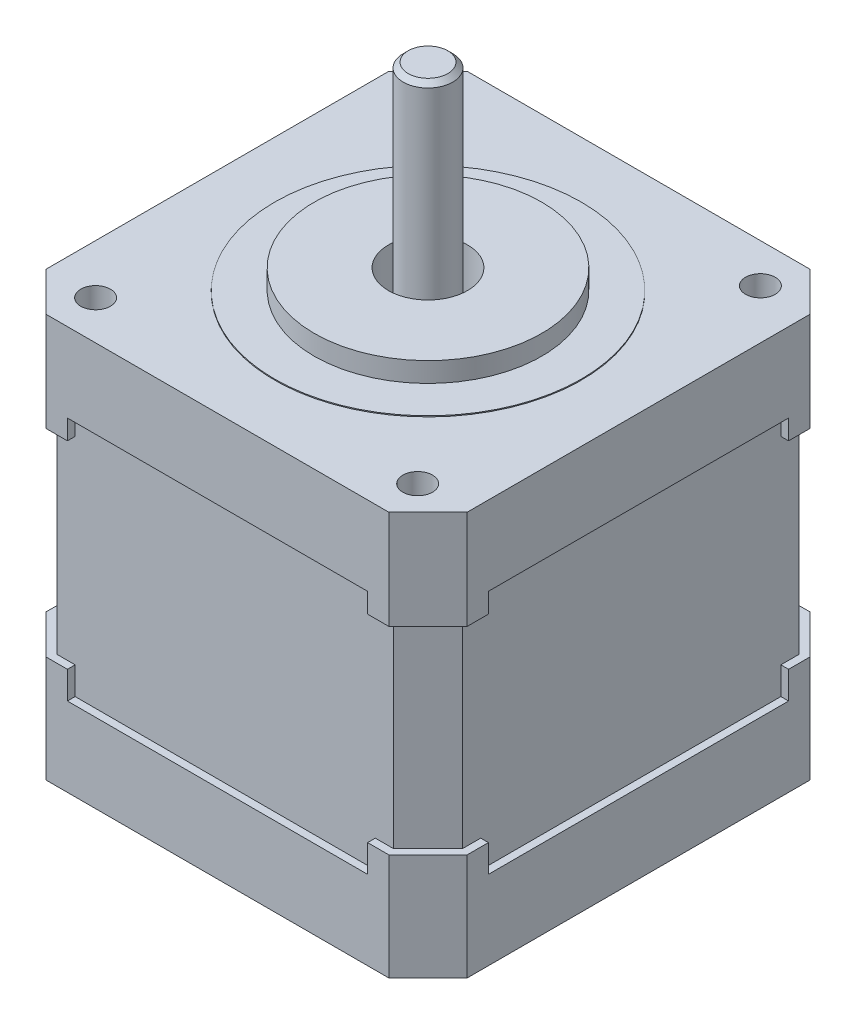
SolidWorks part; units mm, degrees
ref_plane "Alzado" through (0, 0, 0) normal (0, 0, 1) x (1, 0, 0)
ref_plane "Planta" through (0, 0, 0) normal (0, 1, 0) x (1, 0, 0)
ref_plane "Vista lateral" through (0, 0, 0) normal (1, 0, 0) x (0, 0, -1)
sketch "Croquis1" plane through (0, 0, 0) normal (0, 1, 0) x (1, 0, 0)
  line L0 (20.5, 17) -> (17, 20.5)
  line L1 (-17, -20.5) -> (17, -20.5)
  line L2 (-20.5, -17) -> (-20.5, 17)
  line L3 (-17, 20.5) -> (17, 20.5)
  line L4 (20.5, -17) -> (20.5, 17)
  line L5 (-20.5, -20.5) -> (20.5, 20.5) construction
  line L6 (-20.5, 20.5) -> (20.5, -20.5) construction
  line L7 (-20.5, 17) -> (-17, 20.5)
  line L8 (-17, -20.5) -> (-20.5, -17)
  line L9 (17, -20.5) -> (20.5, -17)
  point P0 (0, 0)
  dimension "D1" = 41
  dimension "D2" = 41
extrude "Saliente-Extruir2" add sketch "Croquis1" along normal blind 10
shell "Vaciado6" thickness 0.78
sketch "Croquis2" plane through (21.28, 0, 0) normal (1, 0, 0) x (0, 0, -1)
  line L1 (-17.3231, 10) -> (17.3231, 10) construction
  line L2 (-15.1731, 10) -> (-15.1731, 7.22)
  line L3 (-15.1731, 7.22) -> (15.1731, 7.22)
  line L5 (15.1731, 7.22) -> (15.1731, 10)
  line L6 (-17.3231, 10) -> (-17.3231, -0.78) construction
  line L7 (17.3231, 10) -> (17.3231, -0.78) construction
  line L8 (-17.3231, -0.78) -> (17.3231, -0.78) construction
  line L9 (-15.1731, 10) -> (15.1731, 10)
  dimension "D1" = 2.15
  dimension "D2" = 2.15
  dimension "D3" = 8
extrude "Cortar-Extruir1" cut sketch "Croquis2" against normal through all
sketch "Croquis3" plane through (0, 0, 21.28) normal (0, 0, 1) x (1, 0, 0)
  line L0 (-17.3231, 10) -> (-17.3231, -0.78) construction
  line L1 (-17.3231, 10) -> (17.3231, 10) construction
  line L2 (-15.1731, 10) -> (-15.1731, 7.22)
  line L3 (-15.1731, 7.22) -> (15.1731, 7.22)
  line L4 (15.1731, 7.22) -> (15.1731, 10)
  line L5 (15.1731, 10) -> (-15.1731, 10)
  line L6 (17.3231, 10) -> (17.3231, -0.78) construction
  line L7 (-17.3231, -0.78) -> (17.3231, -0.78) construction
  dimension "D1" = 2.15
  dimension "D2" = 2.15
  dimension "D3" = 8
extrude "Cortar-Extruir2" cut sketch "Croquis3" against normal through all
sketch "Croquis4" plane through (0, 0, 0) normal (0, 1, 0) x (1, 0, 0)
  line L0 (-17, 20.5) -> (17, 20.5)
  line L1 (17, 20.5) -> (20.5, 17)
  line L2 (20.5, 17) -> (20.5, -17)
  line L3 (20.5, -17) -> (17, -20.5)
  line L4 (17, -20.5) -> (-17, -20.5)
  line L5 (-17, -20.5) -> (-20.5, -17)
  line L6 (-20.5, -17) -> (-20.5, 17)
  line L7 (-20.5, 17) -> (-17, 20.5)
extrude "Saliente-Extruir3" add sketch "Croquis4" along normal blind 40
sketch "Croquis5" plane through (0, 40, 0) normal (0, 1, 0) x (1, 0, 0)
  line L0 (-21.28, 17.3231) -> (-17.3231, 21.28)
  line L1 (-17.3231, 21.28) -> (17.3231, 21.28)
  line L2 (17.3231, 21.28) -> (21.28, 17.3231)
  line L3 (21.28, 17.3231) -> (21.28, -17.3231)
  line L4 (21.28, -17.3231) -> (17.3231, -21.28)
  line L5 (17.3231, -21.28) -> (-17.3231, -21.28)
  line L6 (-17.3231, -21.28) -> (-21.28, -17.3231)
  line L7 (-21.28, -17.3231) -> (-21.28, 17.3231)
extrude "Saliente-Extruir4" add sketch "Croquis5" against normal blind 10
sketch "Croquis6" plane through (0, 0, 21.28) normal (0, 0, 1) x (1, 0, 0)
  line L0 (-17.3231, 30) -> (17.3231, 30) construction
  line L1 (-15.1731, 30) -> (15.1731, 30)
  line L2 (-15.1731, 30) -> (-15.1731, 32)
  line L3 (-15.1731, 32) -> (15.1731, 32)
  line L4 (15.1731, 30) -> (15.1731, 32)
  line L5 (-17.3231, 30) -> (-17.3231, 40) construction
  line L6 (17.3231, 30) -> (17.3231, 40) construction
  line L7 (-17.3231, 40) -> (17.3231, 40) construction
  dimension "D1" = 2.15
  dimension "D2" = 2.15
  dimension "D3" = 8
extrude "Cortar-Extruir3" cut sketch "Croquis6" against normal blind 0.78
sketch "Croquis7" plane through (0, 0, -21.28) normal (0, 0, -1) x (-1, 0, 0)
  line L0 (-17.3231, 30) -> (17.3231, 30) construction
  line L1 (-15.1731, 30) -> (15.1731, 30)
  line L2 (-15.1731, 30) -> (-15.1731, 32)
  line L3 (-15.1731, 32) -> (15.1731, 32)
  line L4 (15.1731, 30) -> (15.1731, 32)
  line L5 (17.3231, 30) -> (17.3231, 40) construction
  line L6 (-17.3231, 30) -> (-17.3231, 40) construction
  line L7 (-17.3231, 40) -> (17.3231, 40) construction
  point P8 (-15.1731, 31)
  dimension "D1" = 2.15
  dimension "D2" = 2.15
  dimension "D3" = 8
extrude "Cortar-Extruir4" cut sketch "Croquis7" against normal blind 0.78
sketch "Croquis8" plane through (-21.28, 0, 0) normal (-1, 0, 0) x (0, 0, 1)
  line L0 (-15.1731, 30) -> (-15.1731, 32)
  line L1 (17, 30) -> (-17, 30) construction
  line L2 (-15.1731, 32) -> (15.1731, 32)
  line L3 (15.1731, 32) -> (15.1731, 30)
  line L4 (-17.3231, 30) -> (17.3231, 30) construction
  line L5 (15.1731, 30) -> (-15.1731, 30)
  line L6 (17.3231, 30) -> (17.3231, 40) construction
  line L7 (-17.3231, 30) -> (-17.3231, 40) construction
  line L8 (-17.3231, 40) -> (17.3231, 40) construction
  dimension "D1" = 2.15
  dimension "D2" = 2.15
  dimension "D3" = 8
extrude "Cortar-Extruir5" cut sketch "Croquis8" against normal blind 0.78
sketch "Croquis9" plane through (21.28, 0, 0) normal (1, 0, 0) x (0, 0, -1)
  line L0 (17, 30) -> (-17, 30) construction
  line L1 (-15.1731, 30) -> (15.1731, 30)
  line L2 (-15.1731, 30) -> (-15.1731, 32)
  line L3 (-15.1731, 32) -> (15.1731, 32)
  line L4 (15.1731, 30) -> (15.1731, 32)
  line L5 (-17.3231, 30) -> (-17.3231, 40) construction
  line L6 (17.3231, 30) -> (17.3231, 40) construction
  line L7 (-17.3231, 40) -> (17.3231, 40) construction
  dimension "D1" = 2.15
  dimension "D2" = 2.15
  dimension "D3" = 8
extrude "Cortar-Extruir6" cut sketch "Croquis9" against normal blind 0.78
sketch "Croquis10" plane through (0, 40, 0) normal (0, 1, 0) x (1, 0, 0)
  line L0 (-21.28, 17.3231) -> (-16.28, 17.3231) construction
  line L1 (21.28, 17.3231) -> (16.28, 17.3231) construction
  line L2 (-21.28, -17.3231) -> (-16.28, -17.3231) construction
  line L3 (21.28, -17.3231) -> (16.28, -17.3231) construction
  circle A0 centre (-16.28, 17.3231) radius 1.5
  circle A1 centre (16.28, 17.3231) radius 1.5
  circle A2 centre (16.28, -17.3231) radius 1.5
  circle A3 centre (-16.28, -17.3231) radius 1.5
  dimension "D2" = 3
  dimension "D1" = 5
  dimension "D3" = 5
  dimension "D4" = 2
  dimension "D5" = 2
extrude "Cortar-Extruir7" cut sketch "Croquis10" against normal blind 4
sketch "Croquis11" plane through (0, 40, 0) normal (0, 1, 0) x (1, 0, 0)
  circle A0 centre (0, 0) radius 15.5
  dimension "D1" = 31
extrude "Saliente-Extruir5" add sketch "Croquis11" along normal blind 0.1
sketch "Croquis12" plane through (0, 40.1, 0) normal (0, 1, 0) x (1, 0, 0)
  circle A0 centre (0, 0) radius 11.5
  dimension "D1" = 23
extrude "Saliente-Extruir6" add sketch "Croquis12" along normal blind 2
sketch "Croquis13" plane through (0, 42.1, 0) normal (0, 1, 0) x (1, 0, 0)
  circle A0 centre (0, 0) radius 4
  dimension "D1" = 8
extrude "Cortar-Extruir8" cut sketch "Croquis13" against normal blind 5
sketch "Croquis14" plane through (0, 37.1, 0) normal (0, 1, 0) x (1, 0, 0)
  circle A0 centre (0, 0) radius 2.5
  dimension "D1" = 5
extrude "Saliente-Extruir7" add sketch "Croquis14" along normal blind 23
chamfer "Chaflán1" distance 0.5 angle 45 1 edges at (0, 60.1, 2.5)
